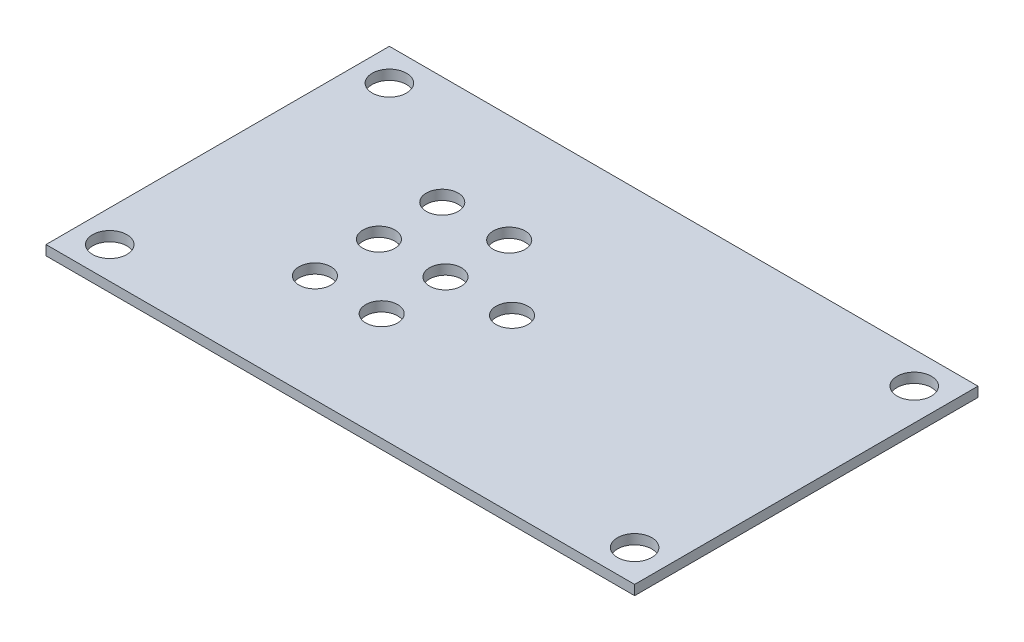
SolidWorks part; units mm, degrees
ref_plane "Front Plane" through (0, 0, 0) normal (0, 0, 1) x (1, 0, 0)
ref_plane "Top Plane" through (0, 0, 0) normal (0, 1, 0) x (1, 0, 0)
ref_plane "Right Plane" through (0, 0, 0) normal (1, 0, 0) x (0, 0, -1)
sketch "Sketch1" plane through (0, 0, 0) normal (0, 1, 0) x (1, 0, 0)
  line L1 (-60, 35) -> (60, 35)
  line L2 (-60, 35) -> (-60, -35)
  line L3 (-60, -35) -> (60, -35)
  line L4 (60, 35) -> (60, -35)
  line L5 (-60, 35) -> (60, -35) construction
  line L6 (-60, -35) -> (60, 35) construction
  point P0 (0, 0)
  dimension "D1" = 120
  dimension "D2" = 70
extrude "Boss-Extrude1" add sketch "Sketch1" along normal blind 2 contours L2 L3 L4 L1
sketch "Sketch3" plane through (0, 2, 0) normal (0, 1, 0) x (1, 0, 0)
  line L0 (-60, 35) -> (-60, -35) construction
  line L1 (-60, 35) -> (60, 35) construction
  line L2 (60, 35) -> (60, -35) construction
  line L3 (-60, -35) -> (60, -35) construction
  circle A0 centre (-53.5, 28.5) radius 3.5
  circle A1 centre (53.5, 28.5) radius 3.5
  circle A2 centre (-53.5, -28.5) radius 3.5
  circle A3 centre (53.5, -28.5) radius 3.5
  point P0 (-53.5, 28.5)
  point P2 (53.5, 28.5)
  point P3 (53.5, -28.5)
  point P4 (-53.5, -28.5)
  dimension "D1" = 6.5
  dimension "D2" = 6.5
  dimension "D3" = 6.5
  dimension "D4" = 6.5
extrude "Cut-Extrude1" cut sketch "Sketch3" against normal blind 3
sketch "Sketch4" plane through (0, 2, 0) normal (0, 1, 0) x (1, 0, 0)
  line L18 (-30.8791, -14.0818) -> (-23.2298, -12.1627) construction
  line L19 (-29.7298, -12.1627) -> (-22.0475, -14.1965) construction
  line L20 (-30.8172, -1.0024) -> (-23.2298, 0.7871) construction
  line L21 (-29.7298, 0.7871) -> (-22.1091, -1.1095) construction
  line L22 (-30.9536, 11.8406) -> (-23.2095, 13.8874) construction
  line L23 (-29.7501, 13.8874) -> (-21.9738, 11.7194) construction
  circle A0 centre (-27.0544, -13.1223) radius 3.25
  circle A1 centre (-27.0235, -0.1076) radius 3.25
  circle A2 centre (-27.0816, 12.864) radius 3.25
  circle A3 centre (-13.5671, 0) radius 3.25
  circle A4 centre (-13.5671, -13) radius 3.25
  circle A5 centre (-13.5671, 13) radius 3.25
  circle A6 centre (0, 0) radius 3.25
  point P0 (-26.5671, -13)
  point P1 (-26.5671, 0)
  point P2 (-26.5671, 13)
  point P3 (-13.5671, -13)
  point P4 (-13.5671, 0)
  point P5 (-13.5671, 13)
  point P6 (0, 0)
  point P7 (-13.5671, 0)
  point P10 (-13.5671, -0.1939)
  point P12 (-13.5671, 13)
  point P13 (-13.5671, -13)
  point P16 (-13.5671, 12.8061)
  point P19 (0, 0)
  point P20 (0, 0)
  point P21 (0, 0)
  point P22 (-26.5671, -13)
  point P27 (-26.5671, 0)
  point P32 (-26.5671, 13)
  point P37 (0, 0)
  point P38 (0, 13)
  point P39 (0, -13)
  point P40 (0, -13)
  point P41 (0, 13)
  point P48 (0, 0)
  point P50 (-13.5671, -13.1939)
  point P52 (0, 0)
  point P53 (0, 0)
  point P54 (0, 0)
  point P55 (0, 0)
  point P56 (0, 0)
  point P57 (0, 0)
sketch "Sketch6" plane through (0, 2, 0) normal (0, 1, 0) x (1, 0, 0)
  circle A0 centre (0, -13) radius 2
  circle A1 centre (0, 13) radius 2
extrude "Boss-Extrude2" add sketch "Sketch6" against normal blind 11
extrude "Cut-Extrude2" cut sketch "Sketch4" against normal blind 11 contours A5 | A3 | A6 | A2 | A1 | A0 | A4
equation "\"D2@Sketch3\"=\"D1@Sketch3\""
equation "\"D3@Sketch3\"=\"D1@Sketch3\""
equation "\"D4@Sketch3\"=\"D1@Sketch3\""
